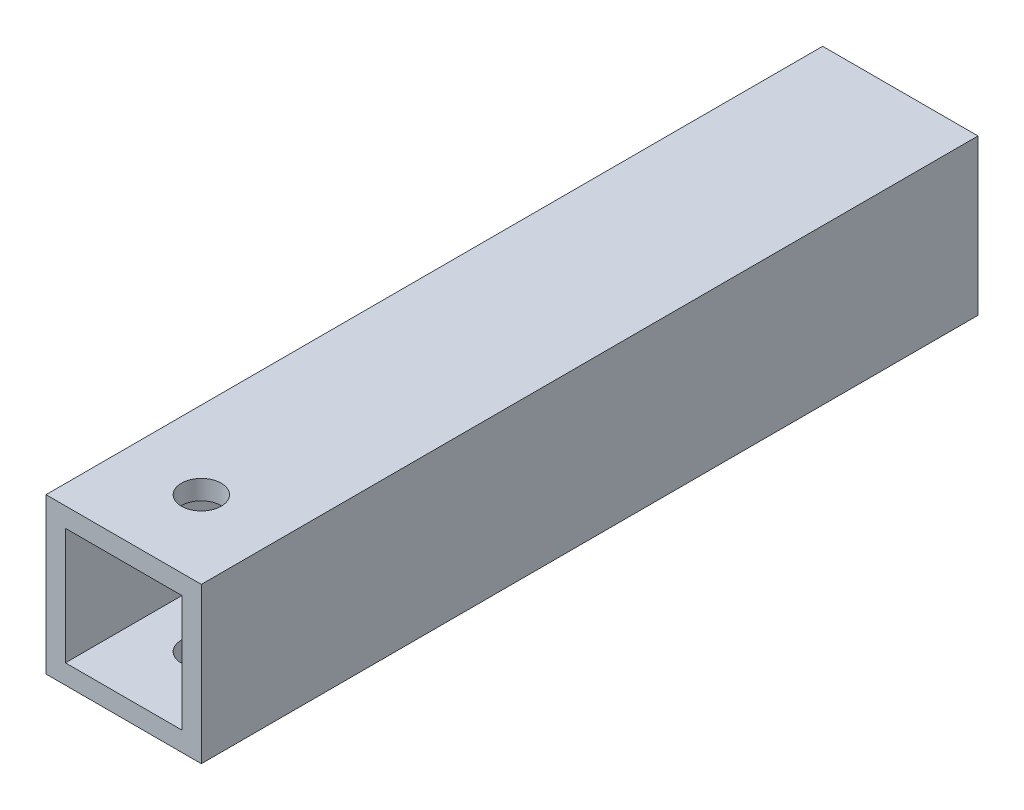
SolidWorks part; units mm, degrees
ref_plane "Front Plane" through (0, 0, 0) normal (0, 0, 1) x (1, 0, 0)
ref_plane "Top Plane" through (0, 0, 0) normal (0, 1, 0) x (1, 0, 0)
ref_plane "Right Plane" through (0, 0, 0) normal (1, 0, 0) x (0, 0, -1)
sketch "Sketch1" plane through (0, 0, 0) normal (0, 0, 1) x (1, 0, 0)
  line L1 (12.7, -12.7) -> (-12.7, -12.7)
  line L2 (12.7, -12.7) -> (12.7, 12.7)
  line L3 (12.7, 12.7) -> (-12.7, 12.7)
  line L4 (-12.7, -12.7) -> (-12.7, 12.7)
  line L5 (12.7, -12.7) -> (-12.7, 12.7) construction
  line L6 (12.7, 12.7) -> (-12.7, -12.7) construction
  point P1 (0, 0)
extrude "Boss-Extrude1" add sketch "Sketch1" along normal blind 127
sketch "Sketch2" plane through (0, 0, 0) normal (0, 0, 1) x (1, 0, 0)
  line L0 (-12.7, 12.7) -> (-12.7, -12.7) construction
  line L1 (9.525, -9.525) -> (-9.525, -9.525)
  line L2 (9.525, -9.525) -> (9.525, 9.525)
  line L3 (9.525, 9.525) -> (-9.525, 9.525)
  line L4 (-9.525, -9.525) -> (-9.525, 9.525)
  line L5 (9.525, -9.525) -> (-9.525, 9.525) construction
  line L6 (9.525, 9.525) -> (-9.525, -9.525) construction
  line L7 (12.7, 12.7) -> (-12.7, 12.7) construction
  point P0 (0, 0)
  dimension "D1" = 3.175
  dimension "D2" = 3.175
extrude "Cut-Extrude1" cut sketch "Sketch2" along normal through all
sketch "Sketch3" plane through (0, 12.7, 0) normal (0, 1, 0) x (1, 0, 0)
  line L0 (12.7, -127) -> (-12.7, -127) construction
  line L1 (12.7, -127) -> (12.7, 0) construction
  circle A0 centre (0, -114.3) radius 3.2639
  dimension "D1" = 12.7
  dimension "D3" = 6.5278
  dimension "D2" = 12.7
extrude "Cut-Extrude2" cut sketch "Sketch3" against normal through all both and the other way through all
